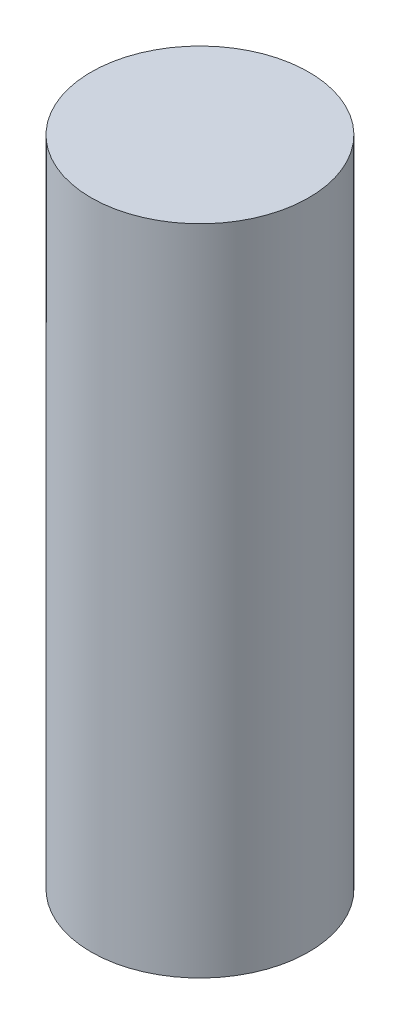
SolidWorks part; units mm, degrees
ref_plane "Front Plane" through (0, 0, 0) normal (0, 0, 1) x (1, 0, 0)
ref_plane "Top Plane" through (0, 0, 0) normal (0, 1, 0) x (1, 0, 0)
ref_plane "Right Plane" through (0, 0, 0) normal (1, 0, 0) x (0, 0, -1)
sketch "Sketch2" plane through (0, 0, 0) normal (0, 1, 0) x (1, 0, 0)
  circle A0 centre (0, 0) radius 5
  dimension "D1" = 10
extrude "Boss-Extrude1" add sketch "Sketch2" along normal blind 30
sketch "Sketch3" plane through (0, 0, 0) normal (0, -1, 0) x (-1, 0, 0)
  circle A0 centre (0, 0) radius 2.5
  dimension "D1" = 5
extrude "Cut-Extrude1" cut sketch "Sketch3" against normal blind 10
sketch "Sketch4" plane through (0, 10, 0) normal (0, -1, 0) x (1, 0, 0)
  line L0 (2, 1.5) -> (2, -1.5)
  circle A0 centre (0, 0) radius 2.5 construction
  arc A1 (2, 1.5) -> (2, -1.5) centre (0, 0) ccw
  dimension "D1" = 3
extrude "Cut-Extrude2" cut sketch "Sketch4" against normal blind 10
